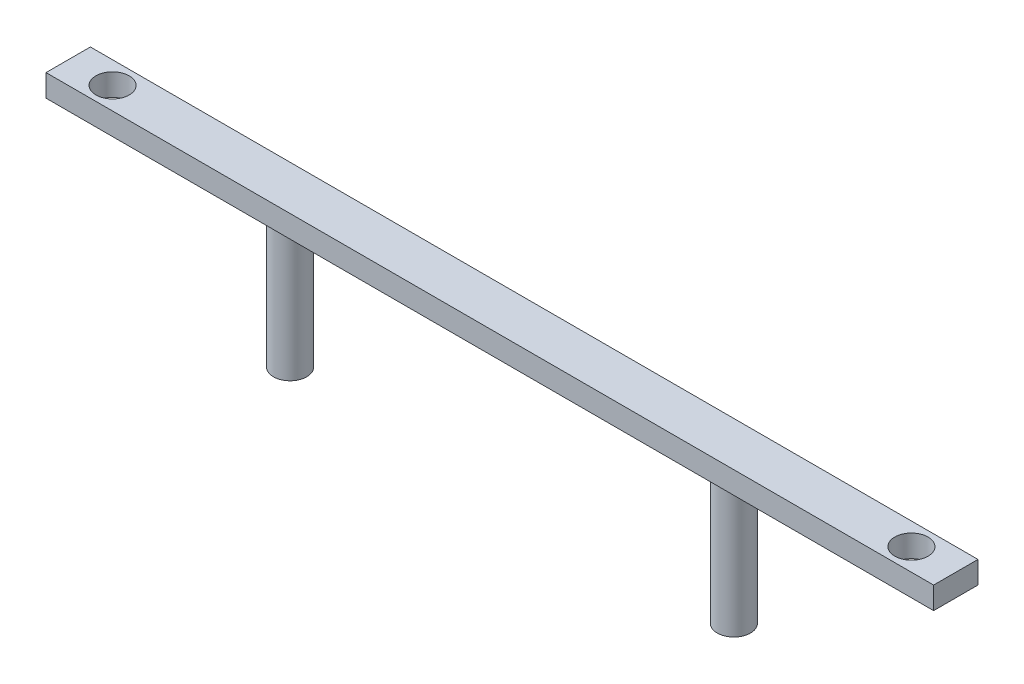
SolidWorks part; units mm, degrees
ref_plane "Front Plane" through (0, 0, 0) normal (0, 0, 1) x (1, 0, 0)
ref_plane "Top Plane" through (0, 0, 0) normal (0, 1, 0) x (1, 0, 0)
ref_plane "Right Plane" through (0, 0, 0) normal (1, 0, 0) x (0, 0, -1)
sketch "Sketch1" plane through (0, 0, 0) normal (0, 1, 0) x (1, 0, 0)
  line L1 (-254, 12.7) -> (254, 12.7)
  line L2 (-254, 12.7) -> (-254, -12.7)
  line L3 (-254, -12.7) -> (254, -12.7)
  line L4 (254, 12.7) -> (254, -12.7)
  line L5 (-254, 12.7) -> (254, -12.7) construction
  line L6 (-254, -12.7) -> (254, 12.7) construction
  point P0 (0, 0)
  dimension "D1" = 508
  dimension "D2" = 25.4
extrude "Boss-Extrude1" add sketch "Sketch1" along normal blind 12.7
sketch "Sketch2" plane through (0, 12.7, 0) normal (0, 1, 0) x (1, 0, 0)
  line L0 (254, 12.7) -> (-254, 12.7) construction
  line L1 (0, 0) -> (0, 166.3935) construction
  line L2 (-254, 12.7) -> (-254, -12.7) construction
  circle A0 centre (-228.6, 0) radius 9.525
  circle A1 centre (228.6, 0) radius 9.525
  dimension "D1" = 25.4
  dimension "D2" = 19.05
  dimension "D3" = 12.7
extrude "Cut-Extrude1" cut sketch "Sketch2" against normal through all
sketch "Sketch3" plane through (0, 0, 0) normal (0, -1, 0) x (1, 0, 0)
  line L0 (0, 0) -> (0, 189.5094) construction
  line L1 (-254, 12.7) -> (254, 12.7) construction
  circle A0 centre (-127, 0) radius 9.525
  circle A1 centre (127, 0) radius 9.525
  dimension "D1" = 19.05
  dimension "D2" = 12.7
  dimension "D3" = 127
extrude "Boss-Extrude2" add sketch "Sketch3" along normal blind 76.2
